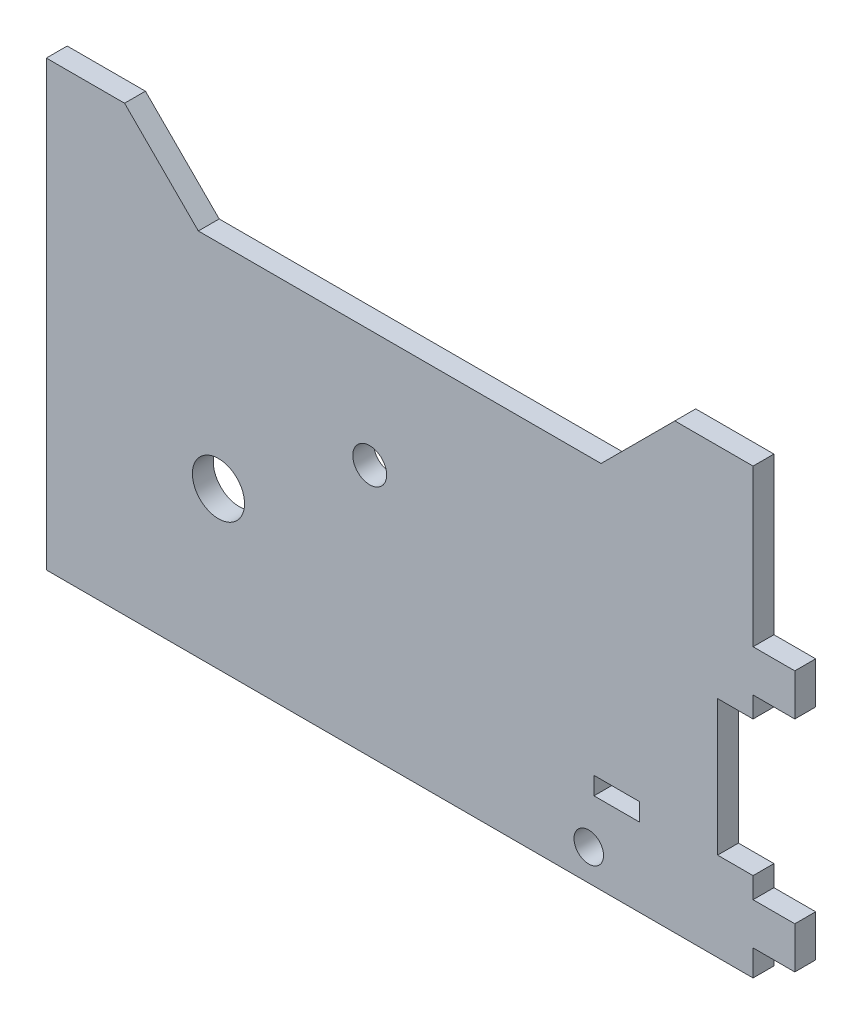
SolidWorks part; units mm, degrees
ref_plane "Front Plane" through (0, 0, 0) normal (0, 0, 1) x (1, 0, 0)
ref_plane "Top Plane" through (0, 0, 0) normal (0, 1, 0) x (1, 0, 0)
ref_plane "Right Plane" through (0, 0, 0) normal (1, 0, 0) x (0, 0, -1)
sketch "Sketch1" plane through (0, 0, 0) normal (0, 0, 1) x (1, 0, 0)
  line L0 (49, 30) -> (56.5, 30)
  line L1 (-79, -30) -> (49, -30)
  line L2 (-79, -30) -> (-79, 30)
  line L3 (-79, 30) -> (49, 30)
  line L6 (56.5, 13) -> (49.7, 13)
  line L7 (49.7, 13) -> (49.7, -13)
  line L8 (49.7, -13) -> (56.5, -13)
  line L10 (56.5, -30) -> (49, -30)
  line L11 (56.5, 30) -> (56.5, 13) construction
  line L12 (56.5, -13) -> (56.5, -30) construction
  line L13 (56.5, 30) -> (56.5, 25)
  line L14 (56.5, 25) -> (64.5, 25)
  line L15 (64.5, 25) -> (64.5, 17)
  line L16 (64.5, 17) -> (56.5, 17)
  line L17 (56.5, 17) -> (56.5, 13)
  line L18 (56.5, -13) -> (56.5, -17)
  line L19 (56.5, -17) -> (64.5, -17)
  line L20 (64.5, -17) -> (64.5, -25)
  line L21 (64.5, -25) -> (56.5, -25)
  line L22 (56.5, -25) -> (56.5, -30)
  line L23 (49, 30) -> (49, -30) construction
  line L24 (26, -11.6) -> (34.7, -11.6)
  line L25 (26, -11.6) -> (26, -15)
  line L26 (26, -15) -> (34.7, -15)
  line L27 (34.7, -11.6) -> (34.7, -15)
  circle A3 centre (-46, 0) radius 5
  circle A4 centre (25, -24) radius 2.83
  circle A5 centre (-17, 18.3961) radius 3.25
  point P1 (-12, 0)
  dimension "D3" = 128
  dimension "D4" = 6
  dimension "D5" = 10
  dimension "D1" = 33
  dimension "D7" = 5
  dimension "D17" = 5.66
  dimension "D18" = 104
  dimension "D25" = 6.5
  dimension "D27" = 29
  dimension "D28" = 18.3961
  dimension "D8" = 26
  dimension "D9" = 5
  dimension "D10" = 7.5
  dimension "D11" = 8
  dimension "D12" = 8
  dimension "D13" = 8.7
  dimension "D14" = 3.4
  dimension "D15" = 15
  dimension "D16" = 15
  dimension "D20" = 4
  dimension "D21" = 4
  dimension "D24" = 8
extrude "Boss-Extrude1" add sketch "Sketch1" along normal blind 4
sketch "Sketch2" plane through (0, 0, 0) normal (0, 0, 1) x (1, 0, 0)
  line L0 (-79, 30) -> (56.5, 30)
  line L1 (56.5, 30) -> (56.5, 55)
  line L2 (56.5, 55) -> (41.5, 55)
  line L3 (41.5, 55) -> (27.3579, 40.8579)
  line L4 (27.3579, 40.8579) -> (-49.8579, 40.8579)
  line L5 (-49.8579, 40.8579) -> (-64, 55)
  line L6 (-64, 55) -> (-79, 55)
  line L7 (-79, 55) -> (-79, 30)
  dimension "D1" = 25
  dimension "D2" = 15
  dimension "D3" = 20
  dimension "D4" = 135
extrude "Boss-Extrude2" add sketch "Sketch2" along normal blind 4
